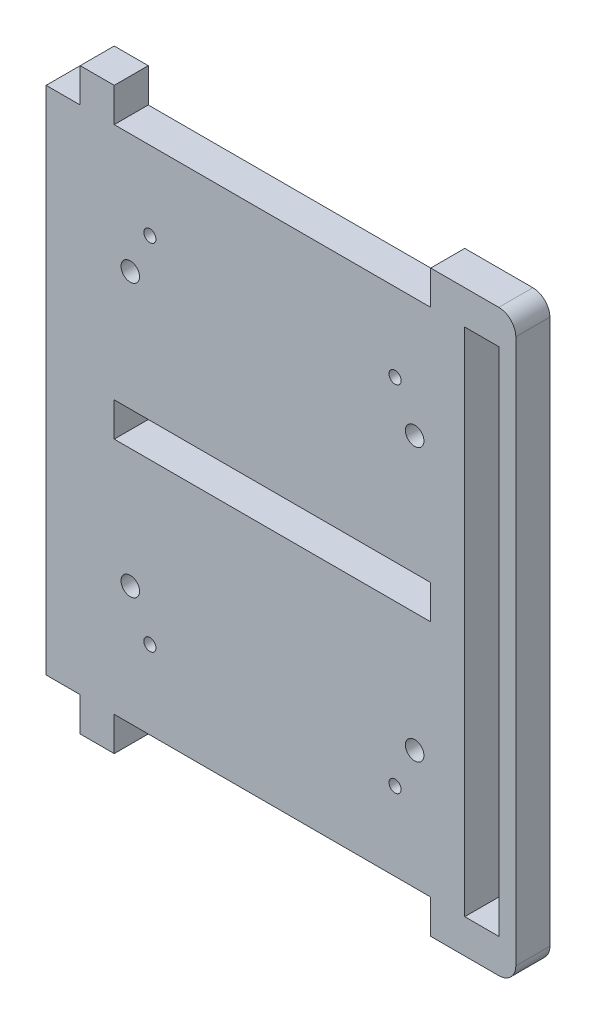
SolidWorks part; units mm, degrees
material "Acrylic (Medium-high impact)"
ref_plane "Front Plane" through (0, 0, 0) normal (0, 0, 1) x (1, 0, 0)
ref_plane "Top Plane" through (0, 0, 0) normal (0, 1, 0) x (1, 0, 0)
ref_plane "Right Plane" through (0, 0, 0) normal (1, 0, 0) x (0, 0, -1)
sketch "Sketch1" plane through (0, 0, 0) normal (0, 0, 1) x (1, 0, 0)
  line L1 (-36.4109, 0) -> (-30.0609, 0)
  line L2 (-36.4109, 0) -> (-36.4109, 6.35)
  line L3 (-36.4109, 107.95) -> (-30.0609, 107.95)
  line L4 (44.8389, 3.175) -> (44.8389, 104.775)
  line L5 (-36.4109, 6.35) -> (-42.7609, 6.35)
  line L7 (-36.4109, 101.6) -> (-42.7609, 101.6)
  line L8 (-42.7609, 6.35) -> (-42.7609, 101.6)
  line L9 (28.9639, 107.95) -> (41.6639, 107.95)
  line L10 (28.9639, 0) -> (41.6639, 0)
  line L11 (-36.4109, 101.6) -> (-36.4109, 107.95)
  line L12 (-30.0609, 101.6) -> (28.9639, 101.6)
  line L13 (28.9639, 101.6) -> (28.9639, 107.95)
  line L14 (28.9639, 107.95) -> (-30.0609, 107.95)
  line L15 (-30.0609, 107.95) -> (-30.0609, 101.6)
  line L16 (-30.0609, 101.6) -> (28.9639, 101.6)
  line L17 (28.9639, 101.6) -> (28.9639, 107.95)
  line L19 (-30.0609, 107.95) -> (-30.0609, 101.6)
  line L20 (-30.0609, 50.8) -> (28.9639, 50.8)
  line L21 (28.9639, 50.8) -> (28.9639, 57.15)
  line L22 (28.9639, 57.15) -> (-30.0609, 57.15)
  line L23 (-30.0609, 57.15) -> (-30.0609, 50.8)
  line L24 (-30.0609, 50.8) -> (28.9639, 50.8)
  line L25 (28.9639, 50.8) -> (28.9639, 57.15)
  line L26 (28.9639, 57.15) -> (-30.0609, 57.15)
  line L27 (-30.0609, 57.15) -> (-30.0609, 50.8)
  line L28 (-30.0609, 0) -> (28.9639, 0)
  line L29 (28.9639, 0) -> (28.9639, 6.35)
  line L30 (28.9639, 6.35) -> (-30.0609, 6.35)
  line L31 (-30.0609, 6.35) -> (-30.0609, 0)
  line L33 (28.9639, 0) -> (28.9639, 6.35)
  line L34 (28.9639, 6.35) -> (-30.0609, 6.35)
  line L35 (-30.0609, 6.35) -> (-30.0609, 0)
  line L37 (35.3139, 101.6) -> (35.3139, 6.35)
  line L38 (35.3139, 6.35) -> (41.6639, 6.35)
  line L39 (41.6639, 6.35) -> (41.6639, 101.6)
  line L40 (41.6639, 101.6) -> (35.3139, 101.6)
  line L41 (35.3139, 101.6) -> (35.3139, 6.35)
  line L42 (35.3139, 6.35) -> (41.6639, 6.35)
  line L43 (41.6639, 6.35) -> (41.6639, 101.6)
  line L44 (41.6639, 101.6) -> (35.3139, 101.6)
  arc A0 (41.6639, 107.95) -> (44.8389, 104.775) centre (41.6639, 104.775) cw
  arc A1 (41.6639, 0) -> (44.8389, 3.175) centre (41.6639, 3.175) ccw
  dimension "D6" = 3.175
  dimension "D1" = 6.35
  dimension "D5" = 3.175
  dimension "D2" = 0
  dimension "D3" = 0
  dimension "D4" = 0
  dimension "D7" = 0
extrude "Boss-Extrude1" add sketch "Sketch1" along normal blind 6.35
hole_wizard "Tap Drill for #8-32 Tap4" positions "Sketch8" profile "Sketch9" hole size "#8-32" standard "ANSI Inch" end condition through all
sketch "Sketch8" plane through (210.2063, -81.8709, 83.3279) normal (0, 0, 1) x (1, 0, 0)
  point P2 (-184.2333, 161.2459)
  point P5 (-184.2333, 110.4459)
  point P8 (-237.2764, 110.4459)
  point P11 (-237.2764, 161.2459)
sketch "Sketch9" plane through (25.9731, 79.375, 83.3279) normal (1, 0, 0) x (0, -1, 0)
  line L0 (0, 0) -> (0, 83.3279)
  line L1 (0, 83.3279) -> (1.7272, 83.3279)
  line L2 (1.7272, 83.3279) -> (1.7272, 0)
  line L3 (1.7272, 0) -> (0, 0)
  line L4 (0, -6.35) -> (0, 107.95) construction
  dimension "Thru Hole Dia." = 3.4544
  dimension "Thru Hole Depth" = 83.3279
hole_wizard "Tap Drill for #8-32 Tap5" positions "Sketch10" profile "Sketch11" hole size "#8-32" standard "ANSI Inch" end condition through all
sketch "Sketch10" plane through (210.2063, -81.8709, 6.35) normal (0, 0, 1) x (1, 0, 0)
  point P2 (-184.2333, 161.2459)
  point P5 (-184.2333, 110.4459)
  point P8 (-237.2764, 110.4459)
  point P11 (-237.2764, 161.2459)
sketch "Sketch11" plane through (25.9731, 79.375, 6.35) normal (1, 0, 0) x (0, -1, 0)
  line L0 (0, 0) -> (0, 6.35)
  line L1 (0, 6.35) -> (1.7272, 6.35)
  line L2 (1.7272, 6.35) -> (1.7272, 0)
  line L3 (1.7272, 0) -> (0, 0)
  line L4 (0, -6.35) -> (0, 107.95) construction
  dimension "Thru Hole Dia." = 3.4544
  dimension "Thru Hole Depth" = 6.35
hole_wizard "Tap Drill for #4-40 Tap1" positions "Sketch12" profile "Sketch13" hole size "#4-40" standard "ANSI Inch" end condition through all
sketch "Sketch12" plane through (210.2063, -81.8709, 0) normal (0, 0, -1) x (-1, 0, 0)
  point P17 (233.6148, 168.8659)
  point P20 (233.6148, 102.8259)
  point P23 (187.8948, 102.8259)
  point P26 (187.8948, 168.8659)
sketch "Sketch13" plane through (-23.4085, 86.995, 0) normal (1, 0, 0) x (0, 1, 0)
  line L0 (0, 0) -> (0, 6.35)
  line L1 (0, 6.35) -> (1.1303, 6.35)
  line L2 (1.1303, 6.35) -> (1.1303, 0)
  line L3 (1.1303, 0) -> (0, 0)
  line L4 (0, -6.35) -> (0, 107.95) construction
  dimension "Thru Hole Dia." = 2.2606
  dimension "Thru Hole Depth" = 6.35
